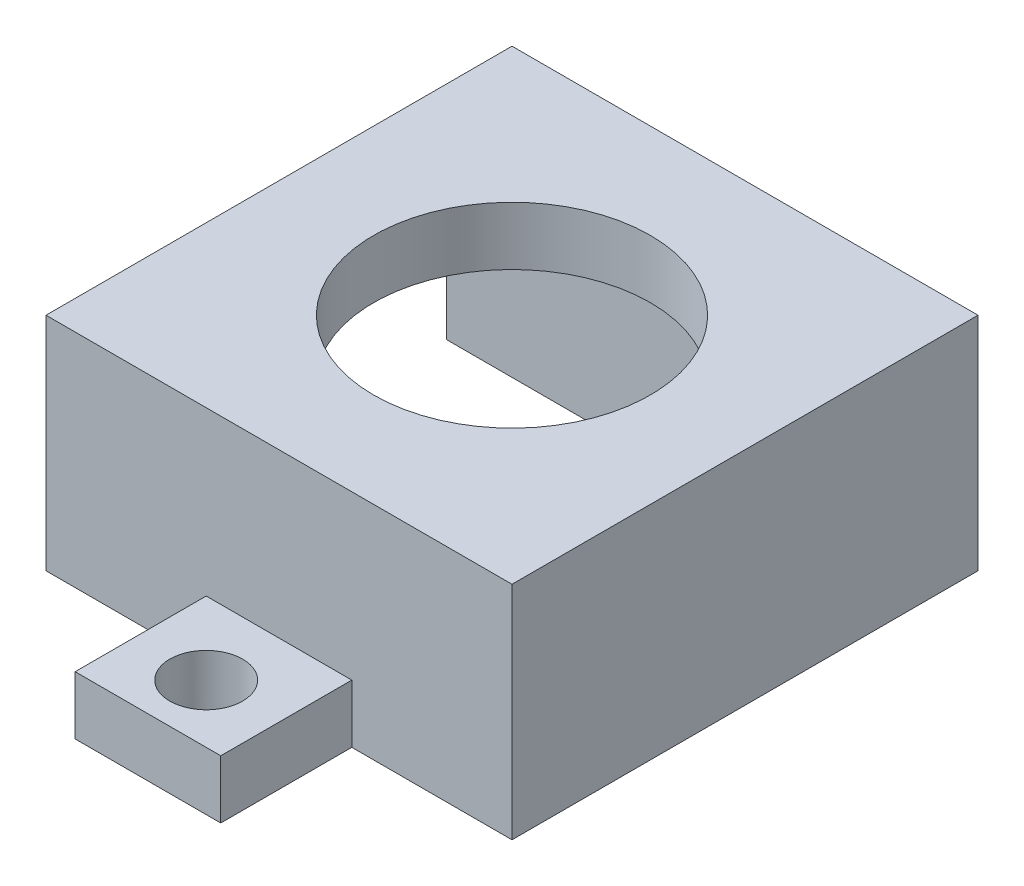
SolidWorks part; units mm, degrees
ref_plane "Front Plane" through (0, 0, 0) normal (0, 0, 1) x (1, 0, 0)
ref_plane "Top Plane" through (0, 0, 0) normal (0, 1, 0) x (1, 0, 0)
ref_plane "Right Plane" through (0, 0, 0) normal (1, 0, 0) x (0, 0, -1)
sketch "Sketch1" plane through (0, 0, 0) normal (0, 1, 0) x (1, 0, 0)
  line L29 (-8, 8) -> (8, 8)
  line L30 (-8, 8) -> (-8, -8)
  line L31 (-8, -8) -> (8, -8)
  line L32 (8, 8) -> (8, -8)
  point P4 (8, 0)
  point P5 (0, 8)
  dimension "D1" = 16
  dimension "D2" = 16
extrude "Boss-Extrude1" add sketch "Sketch1" along normal blind 7.6
sketch "Sketch2" plane through (0, 0, 0) normal (0, 1, 0) x (1, 0, 0)
  line L1 (-5.75, 5.75) -> (5.75, 5.75)
  line L2 (-5.75, 5.75) -> (-5.75, -5.75)
  line L3 (-5.75, -5.75) -> (5.75, -5.75)
  line L4 (5.75, 5.75) -> (5.75, -5.75)
  point P4 (-5.75, 0)
  point P6 (0, 5.75)
  dimension "D1" = 11.5
  dimension "D2" = 11.5
extrude "Cut-Extrude1" cut sketch "Sketch2" along normal blind 5.6
sketch "Sketch3" plane through (0, 0, 0) normal (0, -1, 0) x (1, 0, 0)
  line L0 (-8, -8) -> (-8, 8) construction
  line L1 (-5.75, 5.75) -> (-8, 5.75)
  line L2 (-5.75, 5.75) -> (-5.75, -5.75)
  line L3 (-5.75, -5.75) -> (-8, -5.75)
  line L4 (-8, 5.75) -> (-8, -5.75)
  line L5 (5.75, -5.75) -> (-5.75, -5.75) construction
extrude "Cut-Extrude2" cut sketch "Sketch3" against normal up to surface (5.6 mm away) up to face at (0, 5.6, 0)
sketch "Sketch4" plane through (0, 7.6, 0) normal (0, 1, 0) x (1, 0, 0)
  circle A4 centre (0, 0) radius 4.75
  dimension "D1" = 9.5
extrude "Cut-Extrude3" cut sketch "Sketch4" against normal blind 7.6
sketch "Sketch5" plane through (0, 0, 0) normal (0, 1, 0) x (1, 0, 0)
  line L0 (8, 8) -> (-8, 8) construction
  line L5 (-2.5, 8) -> (2.5, 8)
  line L6 (-2.5, 8) -> (-2.5, 12.5)
  line L7 (-2.5, 12.5) -> (2.5, 12.5)
  line L8 (2.5, 8) -> (2.5, 12.5)
  point P7 (0, 8)
  dimension "D1" = 12.5
  dimension "D2" = 5
extrude "Boss-Extrude2" add sketch "Sketch5" along normal blind 2
sketch "Sketch6" plane through (0, 2, 0) normal (0, 1, 0) x (1, 0, 0)
  circle A0 centre (0, 10.5) radius 1.25
  dimension "D2" = 2.5
  dimension "D1" = 10.5
extrude "Cut-Extrude4" cut sketch "Sketch6" against normal up to next
mirror "Mirror1" about plane through (0, 0, 0) normal (0, 0, 1) of "Boss-Extrude2", "Cut-Extrude4"
equation "\"D1@Sketch6\"= 21/2"
